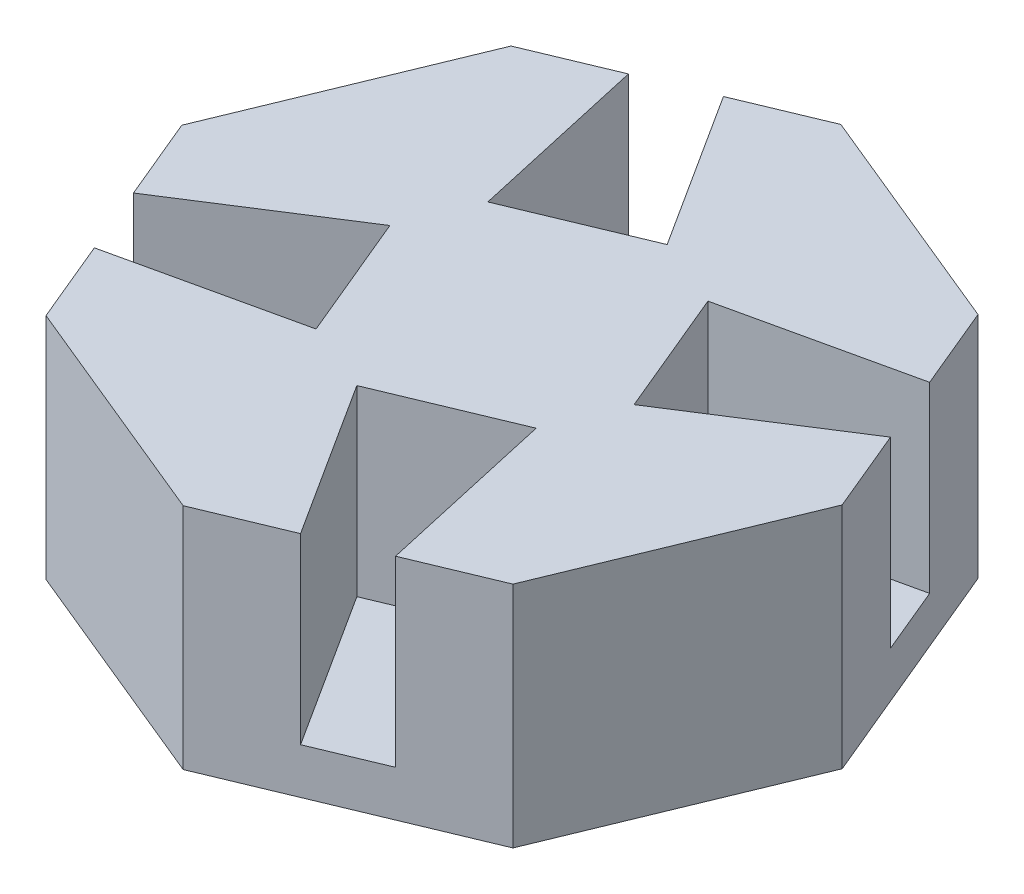
SolidWorks part; units mm, degrees
ref_plane "Front Plane" through (0, 0, 0) normal (0, 0, 1) x (1, 0, 0)
ref_plane "Top Plane" through (0, 0, 0) normal (0, 1, 0) x (1, 0, 0)
ref_plane "Right Plane" through (0, 0, 0) normal (1, 0, 0) x (0, 0, -1)
sketch "Sketch1" plane through (0, 0, 0) normal (0, 1, 0) x (1, 0, 0)
  line L1 (-0.112, 54.9379) -> (-38.9262, 38.7678)
  line L2 (-38.9262, 38.7678) -> (-54.9379, -0.112)
  line L3 (-54.9379, -0.112) -> (-38.7678, -38.9262)
  line L4 (-38.7678, -38.9262) -> (0.112, -54.9379)
  line L5 (0.112, -54.9379) -> (38.9262, -38.7678)
  line L6 (38.9262, -38.7678) -> (54.9379, 0.112)
  line L7 (54.9379, 0.112) -> (38.7678, 38.9262)
  line L8 (38.7678, 38.9262) -> (-0.112, 54.9379)
  circle A0 centre (0, 0) radius 50.7561 construction
  dimension "D2" = 101.5123
  dimension "D1" = 38.8798
  dimension "D3" = 42.0478
extrude "Boss-Extrude1" add sketch "Sketch1" along normal blind 38.1
sketch "Sketch2" plane through (0, 38.1, 0) normal (0, 1, 0) x (1, 0, 0)
  line L0 (19.5191, -46.8529) -> (7.7975, -18.7168) construction
  line L1 (-2.7535, -23.1124) -> (13.9292, -49.1816)
  line L2 (0.112, -54.9379) -> (38.9262, -38.7678) construction
  line L3 (18.3485, -14.3213) -> (25.1089, -44.5241)
  line L4 (-2.7535, -23.1124) -> (18.3485, -14.3213)
  line L5 (-23.1124, 2.7535) -> (-49.1816, -13.9292)
  line L6 (-23.1124, 2.7535) -> (-14.3213, -18.3485)
  line L7 (-14.3213, -18.3485) -> (-44.5241, -25.1089)
  line L8 (-46.8529, -19.5191) -> (-18.7168, -7.7975) construction
  line L9 (2.7535, 23.1124) -> (-13.9292, 49.1816)
  line L10 (2.7535, 23.1124) -> (-18.3485, 14.3213)
  line L11 (-18.3485, 14.3213) -> (-25.1089, 44.5241)
  line L12 (-19.5191, 46.8529) -> (-7.7975, 18.7168) construction
  line L13 (23.1124, -2.7535) -> (49.1816, 13.9292)
  line L14 (23.1124, -2.7535) -> (14.3213, 18.3485)
  line L15 (14.3213, 18.3485) -> (44.5241, 25.1089)
  line L16 (46.8529, 19.5191) -> (18.7168, 7.7975) construction
  point P30 (0, 0)
  line M17 (-0.112, 54.9379) -> (-38.9262, 38.7678)
  line M19 (-54.9379, -0.112) -> (-38.7678, -38.9262)
  line M21 (0.112, -54.9379) -> (38.9262, -38.7678)
  line M23 (54.9379, 0.112) -> (38.7678, 38.9262)
  dimension "D1" = 20.2761
  dimension "D2" = 22.86
  dimension "D3" = 30.48
  dimension "D4" = 80
  dimension "D5" = 80
  dimension "D6" = 4
  dimension "D7" = 14.3213
  dimension "D8" = 11.5678
extrude "Cut-Extrude1" cut sketch "Sketch2" along direction (0, 1, 0) on the side against the normal blind 30.48 contours L4 L1 L3 M21 | L7 L6 L5 M19 | L11 L10 L9 M17 | L15 L14 L13 M23
